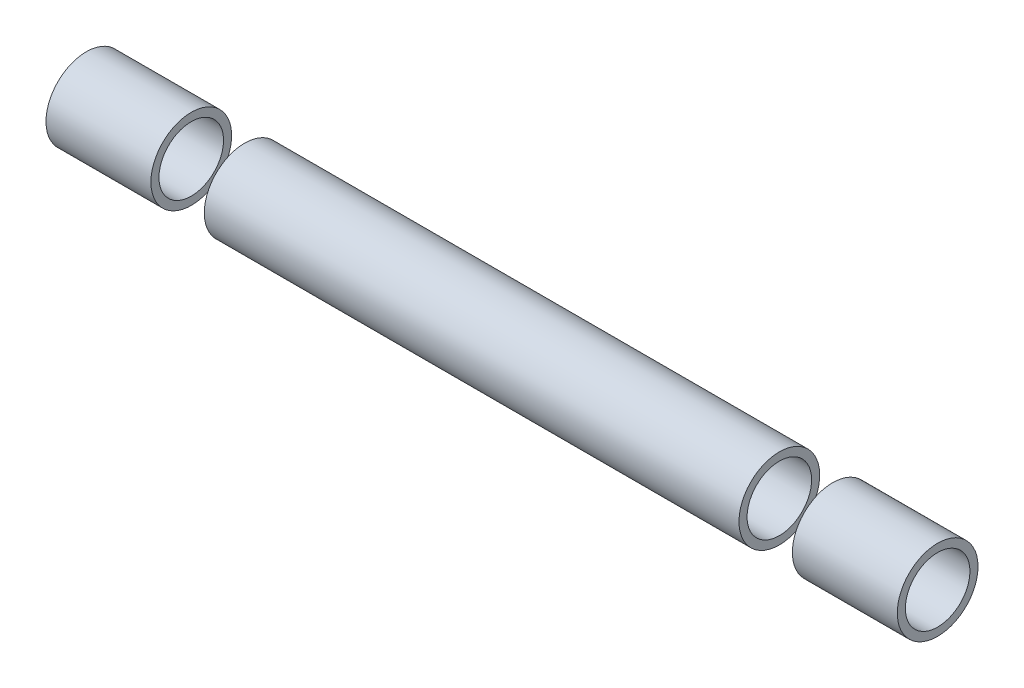
SolidWorks part; units mm, degrees
material "PC High Viscosity"
ref_plane "Front Plane" through (0, 0, 0) normal (0, 0, 1) x (1, 0, 0)
ref_plane "Top Plane" through (0, 0, 0) normal (0, 1, 0) x (1, 0, 0)
ref_plane "Right Plane" through (0, 0, 0) normal (1, 0, 0) x (0, 0, -1)
sketch "Sketch1" plane through (0, 0, 0) normal (1, 0, 0) x (0, 0, -1)
  circle A0 centre (0, 0) radius 15.875
  dimension "D1" = 31.75
extrude "Extrude-Thin1" add sketch "Sketch1" along normal mid plane 334.899 thin thin type one direction reverse wall 3.175
sketch "Sketch2" plane through (0, 0, 0) normal (0, 0, 1) x (1, 0, 0)
  line L0 (-167.4495, -15.875) -> (167.4495, -15.875) construction
  line L1 (105.1745, -15.875) -> (126.1745, -15.875)
  line L2 (105.1745, -15.875) -> (105.1745, 15.875)
  line L3 (105.1745, 15.875) -> (126.1745, 15.875)
  line L4 (126.1745, -15.875) -> (126.1745, 15.875)
  line L5 (167.4495, 15.875) -> (-167.4495, 15.875) construction
  line L6 (167.4495, -15.875) -> (167.4495, 15.875) construction
  line L7 (0, 0) -> (0, 11.1276) construction
  line L8 (-126.1745, -15.875) -> (-126.1745, 15.875)
  line L9 (-105.1745, 15.875) -> (-126.1745, 15.875)
  line L10 (-105.1745, -15.875) -> (-105.1745, 15.875)
  line L11 (-105.1745, -15.875) -> (-126.1745, -15.875)
  dimension "D1" = 41.275
  dimension "D2" = 21
extrude "Cut-Extrude1" cut sketch "Sketch2" against normal through all both and the other way through all
equation "\"D2@Sketch2\"=21mm"
